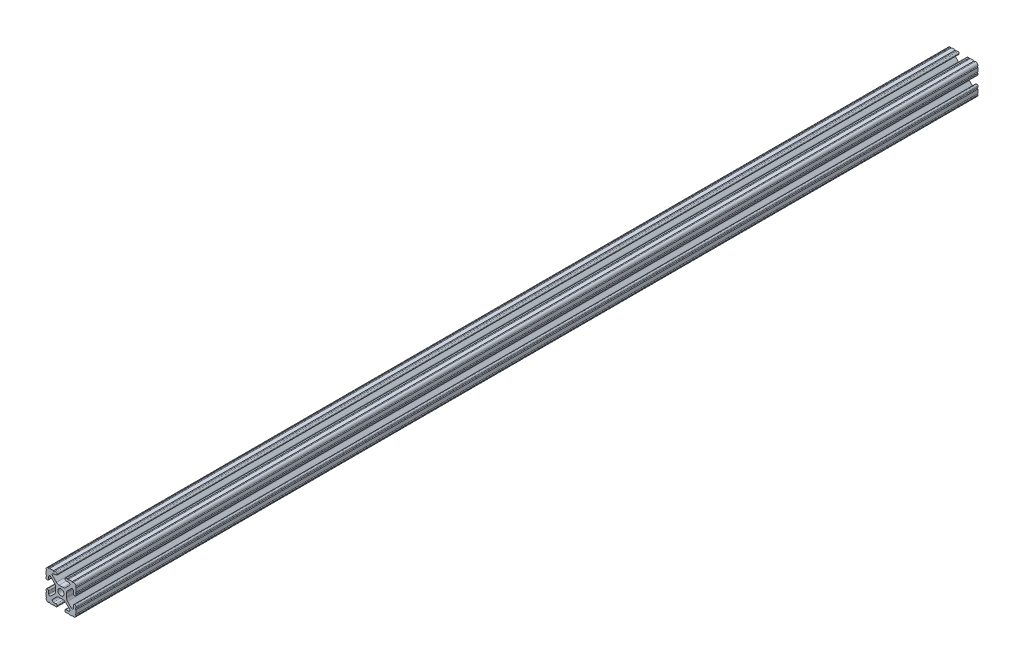
SolidWorks part; units mm, degrees
ref_plane "Front Plane" through (0, 0, 0) normal (0, 0, 1) x (1, 0, 0)
ref_plane "Top Plane" through (0, 0, 0) normal (0, 1, 0) x (1, 0, 0)
ref_plane "Right Plane" through (0, 0, 0) normal (1, 0, 0) x (0, 0, -1)
sketch "Sketch1" plane through (0, 0, 0) normal (0, 0, 1) x (1, 0, 0)
  line L0 (-7.207, 8.7244) -> (-3.8983, 5.4232)
  line L1 (-4.2875, 10.4902) -> (-6.4768, 10.4902)
  line L2 (-3.2385, 11.651) -> (-3.2385, 11.5392)
  line L3 (-5.3171, 12.7) -> (-4.2875, 12.7)
  line L4 (0, 13.4005) -> (0, -14.8534) construction
  line L5 (12.7, 0) -> (-13.9989, 0) construction
  line L6 (-9.5504, 12.7) -> (-6.3331, 12.7)
  line L7 (-12.7, 6.3331) -> (-12.7, 9.5504)
  line L8 (-12.7, 4.2875) -> (-12.7, 5.3171)
  line L9 (-11.5392, 3.2385) -> (-11.651, 3.2385)
  line L10 (-10.4902, 6.4021) -> (-10.4902, 4.2875)
  line L11 (-5.441, 3.8408) -> (-8.7371, 7.1294)
  line L12 (-4.5085, -1.5932) -> (-4.5085, 1.5932)
  line L13 (-1.7093, -4.4958) -> (1.7093, -4.4958)
  line L14 (3.9523, -5.4237) -> (7.1797, -8.6452)
  line L15 (6.4164, -10.4902) -> (4.2875, -10.4902)
  line L16 (3.2385, -11.5392) -> (3.2385, -11.651)
  line L17 (4.2875, -12.7) -> (5.3171, -12.7)
  line L18 (6.3331, -12.7) -> (9.5504, -12.7)
  line L19 (12.7, -9.5504) -> (12.7, -6.3331)
  line L20 (12.7, -5.3171) -> (12.7, -4.2875)
  line L21 (11.651, -3.2385) -> (11.5392, -3.2385)
  line L22 (10.4902, -4.2875) -> (10.4902, -6.4021)
  line L23 (8.7371, -7.1294) -> (5.441, -3.8408)
  line L24 (4.5085, -1.5932) -> (4.5085, 1.5932)
  line L25 (5.441, 3.8408) -> (8.7371, 7.1294)
  line L26 (10.4902, 6.4021) -> (10.4902, 4.2875)
  line L27 (11.5392, 3.2385) -> (11.651, 3.2385)
  line L28 (12.7, 4.2875) -> (12.7, 5.3171)
  line L29 (12.7, 6.3331) -> (12.7, 9.5504)
  line L30 (9.5504, 12.7) -> (6.3331, 12.7)
  line L31 (5.3171, 12.7) -> (4.2875, 12.7)
  line L32 (3.2385, 11.651) -> (3.2385, 11.5392)
  line L33 (4.2875, 10.4902) -> (6.4768, 10.4902)
  line L34 (7.207, 8.7244) -> (3.8983, 5.4232)
  line L35 (1.6558, 4.4958) -> (-1.6558, 4.4958)
  line L36 (-8.7371, -7.1294) -> (-5.441, -3.8408)
  line L37 (-10.4902, -4.2875) -> (-10.4902, -6.4021)
  line L38 (-11.651, -3.2385) -> (-11.5392, -3.2385)
  line L39 (-12.7, -5.3171) -> (-12.7, -4.2875)
  line L40 (-12.7, -9.5504) -> (-12.7, -6.3331)
  line L41 (-6.3331, -12.7) -> (-9.5504, -12.7)
  line L42 (-4.2875, -12.7) -> (-5.3171, -12.7)
  line L43 (-3.2385, -11.5392) -> (-3.2385, -11.651)
  line L44 (-6.4164, -10.4902) -> (-4.2875, -10.4902)
  line L45 (-3.9523, -5.4237) -> (-7.1797, -8.6452)
  arc A0 (-7.207, 8.7244) -> (-6.4768, 10.4902) centre (-6.4768, 9.4563) cw
  arc A1 (-3.2385, 11.5392) -> (-4.2875, 10.4902) centre (-4.2875, 11.5392) cw
  arc A2 (-4.2875, 12.7) -> (-3.2385, 11.651) centre (-4.2875, 11.651) cw
  arc A3 (-5.3171, 12.7) -> (-6.3331, 12.7) centre (-5.8251, 12.7) cw
  arc A4 (-9.5504, 12.7) -> (-10.5664, 12.6998) centre (-10.0584, 12.7) cw
  arc A5 (-12.6998, 10.5664) -> (-10.5664, 12.6998) centre (-10.5918, 10.5918) cw
  arc A6 (-12.6998, 10.5664) -> (-12.7, 9.5504) centre (-12.7, 10.0584) cw
  arc A7 (-12.7, 6.3331) -> (-12.7, 5.3171) centre (-12.7, 5.8251) cw
  arc A8 (-11.651, 3.2385) -> (-12.7, 4.2875) centre (-11.651, 4.2875) cw
  arc A9 (-10.4902, 4.2875) -> (-11.5392, 3.2385) centre (-11.5392, 4.2875) cw
  circle A10 centre (0, 0) radius 2.6035
  arc A11 (-10.4902, 6.4021) -> (-8.7371, 7.1294) centre (-9.4628, 6.4021) cw
  arc A12 (-5.441, 3.8408) -> (-4.5085, 1.5932) centre (-7.6835, 1.5932) cw
  arc A13 (-4.5085, -1.5932) -> (-5.441, -3.8408) centre (-7.6835, -1.5932) cw
  arc A14 (-8.7371, -7.1294) -> (-10.4902, -6.4021) centre (-9.4628, -6.4021) cw
  arc A15 (-1.7093, -4.4958) -> (-3.9523, -5.4237) centre (-1.7093, -7.6708) ccw
  arc A16 (3.9523, -5.4237) -> (1.7093, -4.4958) centre (1.7093, -7.6708) ccw
  arc A17 (6.4164, -10.4902) -> (7.1797, -8.6452) centre (6.4164, -9.4098) ccw
  arc A18 (4.2875, -10.4902) -> (3.2385, -11.5392) centre (4.2875, -11.5392) ccw
  arc A19 (3.2385, -11.651) -> (4.2875, -12.7) centre (4.2875, -11.651) ccw
  arc A20 (6.3331, -12.7) -> (5.3171, -12.7) centre (5.8251, -12.7) ccw
  arc A21 (10.5664, -12.6998) -> (9.5504, -12.7) centre (10.0584, -12.7) ccw
  arc A22 (10.5664, -12.6998) -> (12.6998, -10.5664) centre (10.5918, -10.5918) ccw
  arc A23 (12.7, -9.5504) -> (12.6998, -10.5664) centre (12.7, -10.0584) ccw
  arc A24 (12.7, -5.3171) -> (12.7, -6.3331) centre (12.7, -5.8251) ccw
  arc A25 (12.7, -4.2875) -> (11.651, -3.2385) centre (11.651, -4.2875) ccw
  arc A26 (11.5392, -3.2385) -> (10.4902, -4.2875) centre (11.5392, -4.2875) ccw
  arc A27 (8.7371, -7.1294) -> (10.4902, -6.4021) centre (9.4628, -6.4021) ccw
  arc A28 (4.5085, -1.5932) -> (5.441, -3.8408) centre (7.6835, -1.5932) ccw
  arc A29 (5.441, 3.8408) -> (4.5085, 1.5932) centre (7.6835, 1.5932) ccw
  arc A30 (10.4902, 6.4021) -> (8.7371, 7.1294) centre (9.4628, 6.4021) ccw
  arc A31 (10.4902, 4.2875) -> (11.5392, 3.2385) centre (11.5392, 4.2875) ccw
  arc A32 (11.651, 3.2385) -> (12.7, 4.2875) centre (11.651, 4.2875) ccw
  arc A33 (12.7, 6.3331) -> (12.7, 5.3171) centre (12.7, 5.8251) ccw
  arc A34 (12.6998, 10.5664) -> (12.7, 9.5504) centre (12.7, 10.0584) ccw
  arc A35 (12.6998, 10.5664) -> (10.5664, 12.6998) centre (10.5918, 10.5918) ccw
  arc A36 (9.5504, 12.7) -> (10.5664, 12.6998) centre (10.0584, 12.7) ccw
  arc A37 (5.3171, 12.7) -> (6.3331, 12.7) centre (5.8251, 12.7) ccw
  arc A38 (4.2875, 12.7) -> (3.2385, 11.651) centre (4.2875, 11.651) ccw
  arc A39 (3.2385, 11.5392) -> (4.2875, 10.4902) centre (4.2875, 11.5392) ccw
  arc A40 (7.207, 8.7244) -> (6.4768, 10.4902) centre (6.4768, 9.4563) ccw
  arc A41 (1.6558, 4.4958) -> (3.8983, 5.4232) centre (1.6558, 7.6708) ccw
  arc A42 (-1.6558, 4.4958) -> (-3.8983, 5.4232) centre (-1.6558, 7.6708) cw
  arc A43 (-11.5392, -3.2385) -> (-10.4902, -4.2875) centre (-11.5392, -4.2875) cw
  arc A44 (-12.7, -4.2875) -> (-11.651, -3.2385) centre (-11.651, -4.2875) cw
  arc A45 (-12.7, -5.3171) -> (-12.7, -6.3331) centre (-12.7, -5.8251) cw
  arc A46 (-12.7, -9.5504) -> (-12.6998, -10.5664) centre (-12.7, -10.0584) cw
  arc A47 (-10.5664, -12.6998) -> (-12.6998, -10.5664) centre (-10.5918, -10.5918) cw
  arc A48 (-10.5664, -12.6998) -> (-9.5504, -12.7) centre (-10.0584, -12.7) cw
  arc A49 (-6.3331, -12.7) -> (-5.3171, -12.7) centre (-5.8251, -12.7) cw
  arc A50 (-3.2385, -11.651) -> (-4.2875, -12.7) centre (-4.2875, -11.651) cw
  arc A51 (-4.2875, -10.4902) -> (-3.2385, -11.5392) centre (-4.2875, -11.5392) cw
  arc A52 (-6.4164, -10.4902) -> (-7.1797, -8.6452) centre (-6.4164, -9.4098) cw
  dimension "D1" = 5.207
  dimension "D9" = 14.859
  dimension "D2" = 25.4
  dimension "D3" = 12.7
  dimension "D4" = 6.477
  dimension "D5" = 8.2042
  dimension "D6" = 9.017
  dimension "D8" = 2.2098
  dimension "D10" = 2.2098
extrude "Extrude1" add sketch "Sketch1" against normal blind 762
hole_wizard "#10 Clearance Hole1" positions "Sketch2" profile "Sketch3" hole size "#10" standard "ANSI Inch"
sketch "Sketch2" plane through (0, 4.4958, 0) normal (0, 1, 0) x (1, 0, 0)
  circle A0 centre (5.9531, 396.7607) radius 2.5527 construction
  point P0 (5.9531, 396.7607)
  point P2 (5.9531, 291.9857)
sketch "Sketch3" plane through (5.9531, 4.4958, -396.7607) normal (1, 0, 0) x (0, 0, 1)
  line L0 (0, 0) -> (0, 17.1958)
  line L1 (0, 17.1958) -> (2.8067, 17.1958)
  line L2 (2.8067, 17.1958) -> (2.8067, 0)
  line L5 (2.8067, 0) -> (0, 0)
  line L11 (0, -6.35) -> (0, 107.95) construction
  dimension "Thru Hole Dia." = 5.6134
  dimension "Thru Hole Depth" = 17.1958
